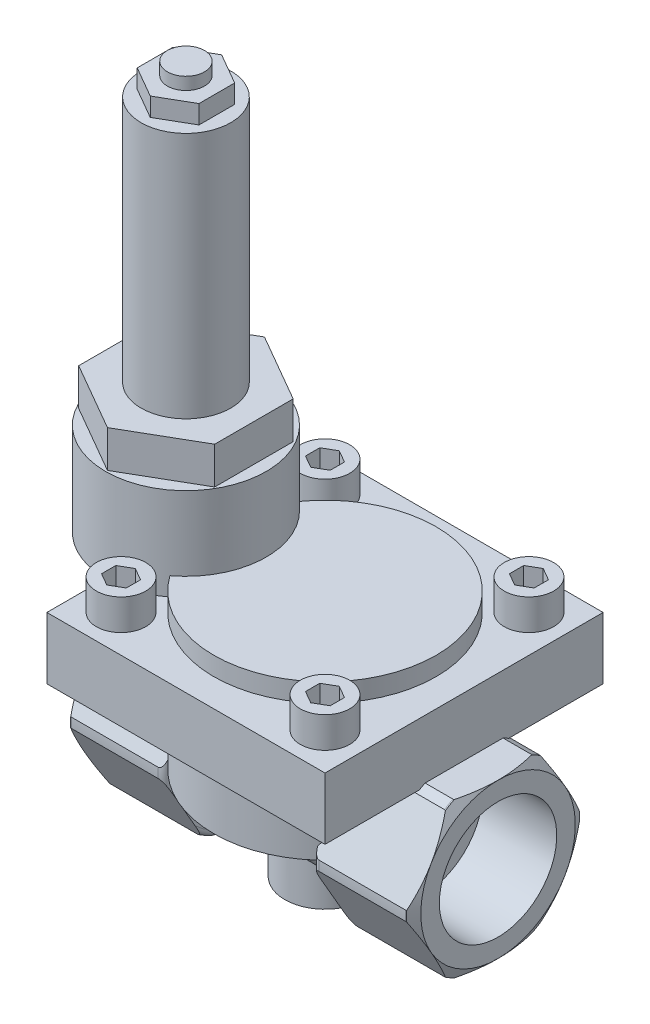
SolidWorks part; units mm, degrees
material "V2a"
ref_plane "Ebene1" through (0, 0, 0) normal (0, 0, 1) x (1, 0, 0)
ref_plane "Ebene2" through (0, 0, 0) normal (0, 1, 0) x (1, 0, 0)
ref_plane "Ebene3" through (0, 0, 0) normal (1, 0, 0) x (0, 0, -1)
sketch "Skizze1" plane through (0, 0, 0) normal (0, 0, 1) x (1, 0, 0)
  line L0 (-52.9316, 0) -> (65.8485, 0) construction
  line L1 (0, -12.3428) -> (0, 14.9638) construction
  line L2 (-11, 10) -> (11, 10)
  line L3 (-12, 13) -> (-12, 11)
  line L4 (-13, 14) -> (-27, 14)
  line L5 (-28, 13) -> (-28, 9.5)
  line L6 (-28, 9.5) -> (-16, 9.5)
  line L7 (-16, 9.5) -> (-16, 7)
  line L8 (-16, 7) -> (16, 7)
  line L9 (1.2147, -11.3241) -> (1.2147, -12.3428) construction
  line L10 (16, 9.5) -> (16, 7)
  line L11 (28, 9.5) -> (16, 9.5)
  line L12 (28, 13) -> (28, 9.5)
  line L13 (13, 14) -> (27, 14)
  line L14 (12, 13) -> (12, 11)
  arc A0 (-27, 14) -> (-28, 13) centre (-27, 13) ccw
  arc A1 (-12, 13) -> (-13, 14) centre (-13, 13) ccw
  arc A2 (-12, 11) -> (-11, 10) centre (-11, 11) ccw
  arc A3 (12, 11) -> (11, 10) centre (11, 11) cw
  arc A4 (12, 13) -> (13, 14) centre (13, 13) cw
  arc A5 (27, 14) -> (28, 13) centre (27, 13) cw
  point P26 (-12, 14)
  point P33 (0, 7)
  point P35 (0, 10)
  dimension "D6" = 12
  dimension "D9" = 20
  dimension "D1" = 1
  dimension "D7" = 1
  dimension "D2" = 16
  dimension "D3" = 56
  dimension "D4" = 28
  dimension "D5" = 19
  dimension "D8" = 14
revolve "Basis-Rotation" add sketch "Skizze1" angle 360 about L0
sketch "Skizze2" plane through (-28, 0, 0) normal (-1, 0, 0) x (0, 0, 1)
  line L0 (39.2437, 0) -> (-39.2437, 0) construction
  line L1 (14.4338, 0) -> (7.2169, 12.5)
  line L2 (7.2169, 12.5) -> (-7.2169, 12.5)
  line L3 (-7.2169, 12.5) -> (-14.4338, 0)
  line L4 (-14.4338, 0) -> (-7.2169, -12.5)
  line L5 (-7.2169, -12.5) -> (7.2169, -12.5)
  line L6 (7.2169, -12.5) -> (14.4338, 0)
  circle A0 centre (0, 0) radius 12.5 construction
  dimension "D1" = 25
extrude "Schnitt-Linear austragen1" cut sketch "Skizze2" against normal up to surface (16 mm away) flip side to cut up to face at (-12, 0, 13)
mirror "Spiegeln1" about plane through (0, 0, 0) normal (1, 0, 0) of "Schnitt-Linear austragen1"
sketch "Skizze3" plane through (-28, 0, 0) normal (-1, 0, 0) x (0, 0, 1)
  line L0 (3.5707, 12.5) -> (-3.5707, 12.5) construction
  circle A0 centre (0, 0) radius 12.5
extrude "Schnitt-Linear austragen2" cut sketch "Skizze3" against normal blind 48 draft 61 flip side to cut
mirror "Spiegeln2" about plane through (0, 0, 0) normal (1, 0, 0) of "Schnitt-Linear austragen2"
sketch "Skizze4" plane through (0, 0, 0) normal (0, 1, 0) x (1, 0, 0)
  circle A0 centre (0, 0) radius 18
  dimension "D1" = 36
extrude "Aufsatz-Linear austragen1" add sketch "Skizze4" along normal blind 25
sketch "Skizze5" plane through (0, 0, 0) normal (0, 1, 0) x (1, 0, 0)
  circle A0 centre (0, 0) radius 6.5
  dimension "D1" = 13
extrude "Aufsatz-Linear austragen2" add sketch "Skizze5" against normal blind 15
ref_plane "Ebene4" through (0, 12, 0) normal (0, 1, 0) x (-1, 0, 0)
sketch "Skizze6" plane through (0, 12, 0) normal (0, 1, 0) x (-1, 0, 0)
  line L0 (0, 15.9467) -> (0, -26.8267) construction
  line L1 (-22.5, 22.5) -> (22.5, 22.5)
  line L2 (-22.5, 22.5) -> (-22.5, -22.5)
  line L3 (-22.5, -22.5) -> (22.5, -22.5)
  line L4 (22.5, 22.5) -> (22.5, -22.5)
  line L5 (19.7333, 0) -> (-16.4267, 0) construction
  line L6 (27.1773, 0) -> (28, 0) construction
  dimension "D1" = 45
  dimension "D2" = 45
extrude "Aufsatz-Linear austragen3" add sketch "Skizze6" along normal blind 10
sketch "Skizze7" plane through (0, 22, 0) normal (0, 1, 0) x (-1, 0, 0)
  line L0 (0, 25.6784) -> (0, -26.886) construction
  line L1 (-24.64, 0) -> (25.6, 0) construction
  line L2 (22.5, 22.5) -> (-22.5, 22.5) construction
  line L3 (-22.5, 22.5) -> (-22.5, -22.5) construction
  circle A0 centre (-16.5, 16.5) radius 4
  circle A1 centre (16.5, 16.5) radius 4
  circle A2 centre (16.5, -16.5) radius 4
  circle A3 centre (-16.5, -16.5) radius 4
  dimension "D1" = 8
  dimension "D2" = 6
  dimension "D3" = 6
extrude "Aufsatz-Linear austragen4" add sketch "Skizze7" along normal blind 5
sketch "Skizze8" plane through (0, 27, 0) normal (0, 1, 0) x (-1, 0, 0)
  line L0 (0, 50) -> (0, -50) construction
  line L1 (-16.5, 14.1906) -> (-14.5, 15.3453)
  line L2 (-14.5, 15.3453) -> (-14.5, 17.6547)
  line L3 (-14.5, 17.6547) -> (-16.5, 18.8094)
  line L4 (-16.5, 18.8094) -> (-18.5, 17.6547)
  line L5 (-18.5, 17.6547) -> (-18.5, 15.3453)
  line L6 (-18.5, 15.3453) -> (-16.5, 14.1906)
  line L7 (0, 20.584) -> (0, -23.6982) construction
  line L8 (-21.5467, 0) -> (22.5, 0) construction
  line L9 (22.5, -22.5) -> (22.5, 22.5) construction
  line L10 (14.5, 17.6547) -> (16.5, 18.8094)
  line L11 (14.5, 15.3453) -> (14.5, 17.6547)
  line L12 (16.5, 18.8094) -> (18.5, 17.6547)
  line L13 (18.5, 17.6547) -> (18.5, 15.3453)
  line L14 (18.5, 15.3453) -> (16.5, 14.1906)
  line L15 (16.5, 14.1906) -> (14.5, 15.3453)
  line L16 (16.5, -14.1906) -> (14.5, -15.3453)
  line L17 (18.5, -15.3453) -> (16.5, -14.1906)
  line L18 (18.5, -17.6547) -> (18.5, -15.3453)
  line L19 (16.5, -18.8094) -> (18.5, -17.6547)
  line L20 (14.5, -15.3453) -> (14.5, -17.6547)
  line L21 (14.5, -17.6547) -> (16.5, -18.8094)
  line L22 (-18.5, -15.3453) -> (-16.5, -14.1906)
  line L23 (-18.5, -17.6547) -> (-18.5, -15.3453)
  line L24 (-16.5, -18.8094) -> (-18.5, -17.6547)
  line L25 (-14.5, -17.6547) -> (-16.5, -18.8094)
  line L26 (-14.5, -15.3453) -> (-14.5, -17.6547)
  line L27 (-16.5, -14.1906) -> (-14.5, -15.3453)
  circle A0 centre (-16.5, 16.5) radius 2 construction
  circle A1 centre (16.5, 16.5) radius 2 construction
  circle A2 centre (16.5, -16.5) radius 2 construction
  circle A3 centre (-16.5, -16.5) radius 2 construction
  dimension "D1" = 4
extrude "Schnitt-Linear austragen3" cut sketch "Skizze8" against normal blind 3
sketch "Skizze9" plane through (0, 22, 0) normal (0, 1, 0) x (-1, 0, 0)
  line L0 (22.5, -22.5) -> (22.5, 22.5) construction
  circle A0 centre (22.5, 0) radius 13
  dimension "D1" = 26
extrude "Aufsatz-Linear austragen5" add sketch "Skizze9" along normal blind 15
sketch "Skizze10" plane through (0, 37, 0) normal (0, 1, 0) x (-1, 0, 0)
  line L0 (0, 50) -> (0, -50) construction
  line L1 (22.5, -12.7017) -> (33.5, -6.3509)
  line L2 (33.5, -6.3509) -> (33.5, 6.3509)
  line L3 (33.5, 6.3509) -> (22.5, 12.7017)
  line L4 (22.5, 12.7017) -> (11.5, 6.3509)
  line L5 (11.5, 6.3509) -> (11.5, -6.3509)
  line L6 (11.5, -6.3509) -> (22.5, -12.7017)
  circle A0 centre (22.5, 0) radius 11 construction
  dimension "D1" = 22
extrude "Aufsatz-Linear austragen6" add sketch "Skizze10" along normal blind 6
sketch "Skizze11" plane through (0, 43, 0) normal (0, 1, 0) x (1, 0, 0)
  circle A0 centre (-22.5, 0) radius 7.25
  dimension "D1" = 14.5
extrude "Aufsatz-Linear austragen7" add sketch "Skizze11" along normal blind 40
sketch "Skizze12" plane through (0, 83, 0) normal (0, 1, 0) x (1, 0, 0)
  circle A0 centre (-22.5, 0) radius 3
  circle A1 centre (-22.5, 0) radius 7.25 construction
  dimension "D1" = 6
extrude "Aufsatz-Linear austragen8" add sketch "Skizze12" along normal blind 5
sketch "Skizze13" plane through (0, 83, 0) normal (0, 1, 0) x (1, 0, 0)
  line L0 (-11.5, -6.3509) -> (-11.5, 6.3509) construction
  line L1 (-17.5, -2.8868) -> (-17.5, 2.8868)
  line L2 (-17.5, 2.8868) -> (-22.5, 5.7735)
  line L3 (-22.5, 5.7735) -> (-27.5, 2.8868)
  line L4 (-27.5, 2.8868) -> (-27.5, -2.8868)
  line L5 (-27.5, -2.8868) -> (-22.5, -5.7735)
  line L6 (-22.5, -5.7735) -> (-17.5, -2.8868)
  circle A0 centre (-22.5, 0) radius 5 construction
  dimension "D1" = 10
extrude "Aufsatz-Linear austragen9" add sketch "Skizze13" along normal blind 3
